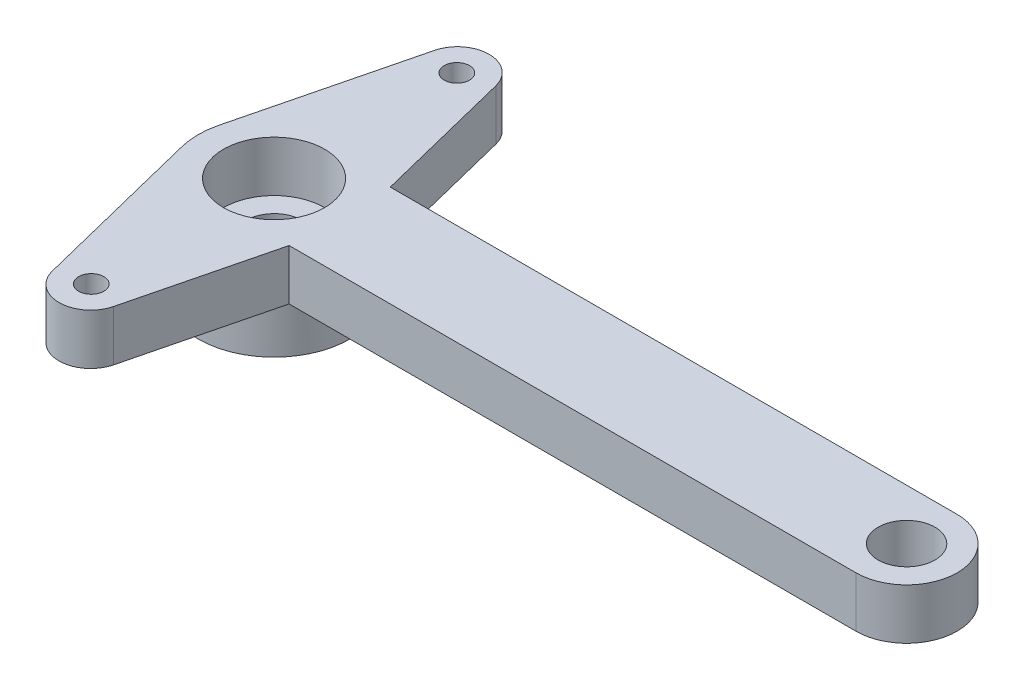
SolidWorks part; units mm, degrees
ref_plane "Front Plane" through (0, 0, 0) normal (0, 0, 1) x (1, 0, 0)
ref_plane "Top Plane" through (0, 0, 0) normal (0, 1, 0) x (1, 0, 0)
ref_plane "Right Plane" through (0, 0, 0) normal (1, 0, 0) x (0, 0, -1)
sketch "Sketch1" plane through (0, 0, 0) normal (0, 1, 0) x (1, 0, 0)
  line L0 (0, 0) -> (0, 50000) construction
  line L1 (0, 0) -> (50000, 0) construction
  line L2 (0, 17) -> (50000, 17) construction
  line L3 (-5.8226, 1.4483) -> (-2.4261, 15.1034)
  line L4 (5.8226, 1.4483) -> (2.4261, 15.1034)
  line L5 (5.8226, -1.4483) -> (2.4261, -15.1034)
  line L6 (-5.8226, -1.4483) -> (-2.4261, -15.1034)
  arc A0 (-5.8226, 1.4483) -> (-5.8226, -1.4483) centre (0, 0) ccw
  circle A1 centre (0, 0) radius 2.25
  arc A2 (2.4261, 15.1034) -> (-2.4261, 15.1034) centre (0, 14.5) ccw
  arc A3 (2.4261, -15.1034) -> (-2.4261, -15.1034) centre (0, -14.5) cw
  arc A4 (5.8226, -1.4483) -> (5.8226, 1.4483) centre (0, 0) ccw
  point P16 (4.0806, 4.3987)
  dimension "D1" = 4.5
  dimension "D2" = 12
  dimension "D4" = 5
  dimension "D3" = 17
extrude "Boss-Extrude1" add sketch "Sketch1" along normal blind 8
sketch "Sketch2" plane through (0, 0, 0) normal (0, -1, 0) x (1, 0, 0)
  line L0 (0, 0) -> (0, -50000) construction
  line L1 (0, 0) -> (-50000, 0) construction
  line L2 (0, -14.45) -> (-50000, -14.45) construction
  circle A0 centre (0, -14.45) radius 1
  circle A1 centre (0, 14.45) radius 1
  dimension "D2" = 2
  dimension "D1" = 14.45
extrude "Cut-Extrude1" cut sketch "Sketch2" against normal blind 10
sketch "Sketch3" plane through (0, 0, 0) normal (1, 0, 0) x (0, 0, -1)
  line L0 (0, 0) -> (0, 50000) construction
  line L1 (0, 0) -> (-50000, 0) construction
  line L3 (6, 0) -> (18, 0)
  line L4 (6, 0) -> (6, 4)
  line L5 (6, 4) -> (18, 4)
  line L6 (18, 0) -> (18, 4)
  dimension "D1" = 6
  dimension "D2" = 12
  dimension "D3" = 4
revolve "Cut-Revolve1" cut sketch "Sketch3" angle 360 about L0
sketch "Sketch4" plane through (0, 8, 0) normal (0, 1, 0) x (1, 0, 0)
  line L0 (0, 0) -> (50000, 0) construction
  line L1 (0, 0) -> (0, 50000) construction
  line L2 (50, 4) -> (5.1879, 4)
  line L3 (5.8226, 1.4483) -> (2.4261, 15.1034) construction
  line L4 (50, -4) -> (5.1879, -4)
  line L5 (5.1879, 4) -> (5.1879, -4)
  circle A0 centre (50, 0) radius 2.25
  arc A1 (50, -4) -> (50, 4) centre (50, 0) ccw
  dimension "D1" = 4.5
  dimension "D2" = 8
  dimension "D3" = 50
extrude "Boss-Extrude2" add sketch "Sketch4" against normal blind 4
sketch "Sketch5" plane through (0, 8, 0) normal (0, 1, 0) x (1, 0, 0)
  circle A0 centre (0, 0) radius 4
  dimension "D1" = 8
extrude "Cut-Extrude2" cut sketch "Sketch5" against normal blind 4
